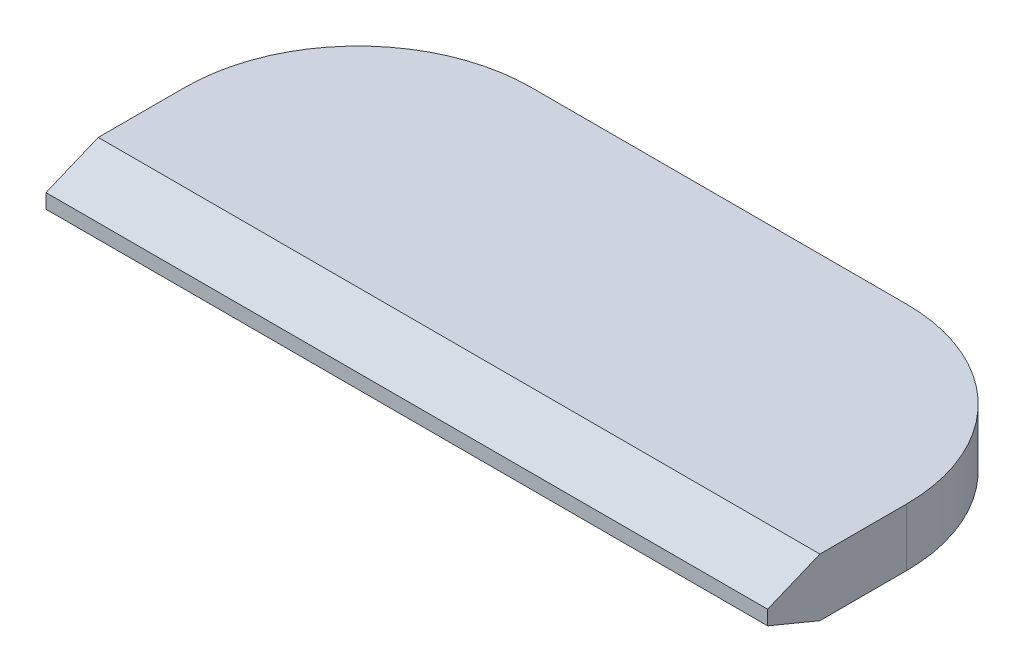
SolidWorks part; units mm, degrees
ref_plane "Top" through (0, 0, 0) normal (0, 0, 1) x (1, 0, 0)
ref_plane "Front" through (0, 0, 0) normal (0, 1, 0) x (1, 0, 0)
ref_plane "Right" through (0, 0, 0) normal (1, 0, 0) x (0, 0, -1)
sketch "Profile Sketch" plane through (0, 0, 0) normal (0, 1, 0) x (1, 0, 0)
  line L0 (0, 1.8107) -> (25, 1.8107) construction
  line L1 (0, 0) -> (25, 0)
  line L2 (0, 0) -> (0, 10.8107)
  line L3 (0, 10.8107) -> (25, 10.8107)
  line L4 (25, 0) -> (25, 10.8107)
  dimension "D1" = 25
  dimension "D2" = 9
  dimension "D3" = 1.8107
extrude "Thickness Extrude" add sketch "Profile Sketch" along normal blind 2
fillet "Fillets" radius 6 2 edges at (25, 1, -10.8107) (0, 1, -10.8107)
chamfer "Connection Chamfer" distance 0.75 angle 67.5 2 edges at (12.5, 0, 0) (12.5, 2, 0)
equation "\"D3@Profile Sketch\"=\"Connection Chamfer Size\"*tan(\"Connection Chamfer Angle\")"
equation "\"Connection Chamfer Size\"= ( \"Handle Thickness\" - \"Base Width\" ) / 2"
equation "\"D1@Connection Chamfer\"=\"Connection Chamfer Size\""
equation "\"Handle Thickness\"= 2"
equation "\"D1@Thickness Extrude\"=\"Handle Thickness\""
equation "\"Connection Chamfer Angle\"= 67.5deg"
equation "\"D2@Connection Chamfer\"=\"Connection Chamfer Angle\""
equation "\"Base Width\" = 0.5"
